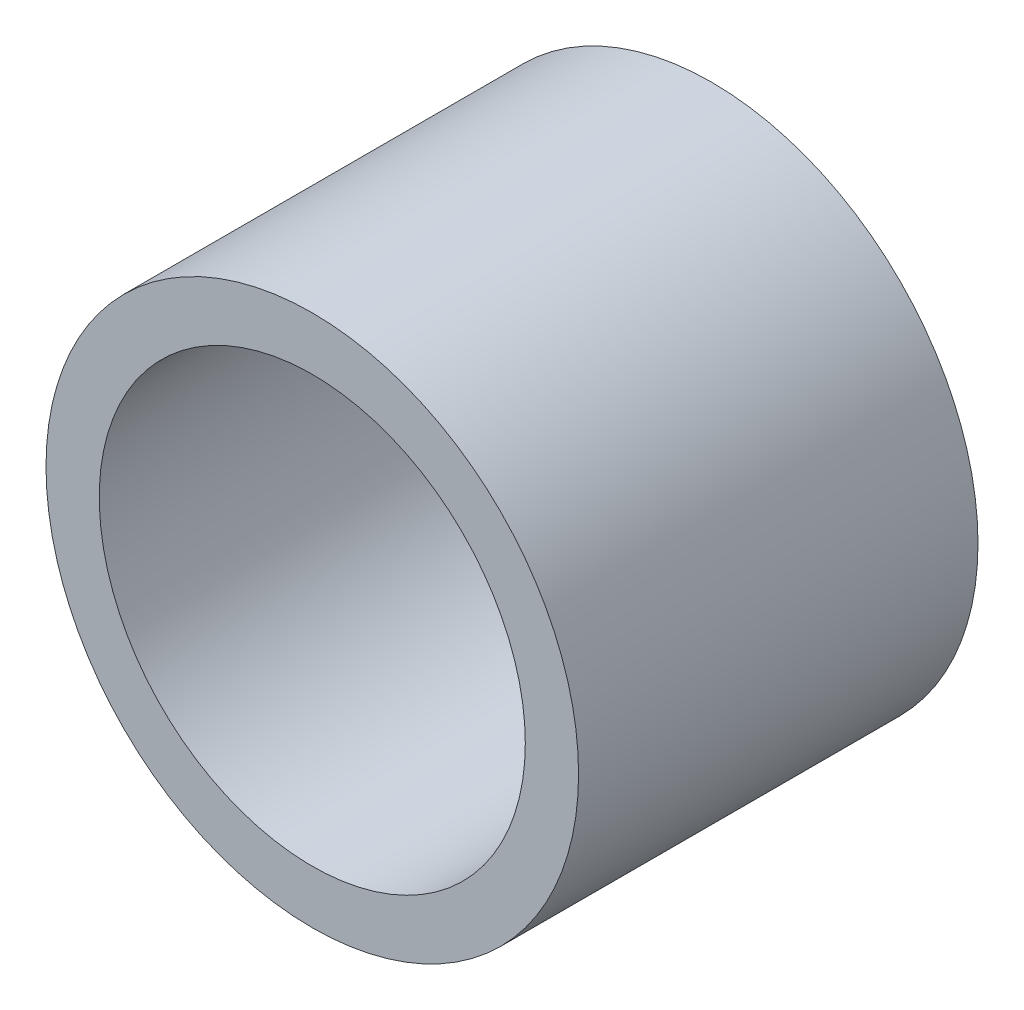
SolidWorks part; units mm, degrees
ref_plane "Front Plane" through (0, 0, 0) normal (0, 0, 1) x (1, 0, 0)
ref_plane "Top Plane" through (0, 0, 0) normal (0, 1, 0) x (1, 0, 0)
ref_plane "Right Plane" through (0, 0, 0) normal (1, 0, 0) x (0, 0, -1)
sketch "Sketch1" plane through (0, 0, 0) normal (0, 0, 1) x (1, 0, 0)
  circle A3 centre (0, 0) radius 10
  circle A4 centre (0, 0) radius 8
extrude "Boss-Extrude1" add sketch "Sketch1" along normal blind 15
